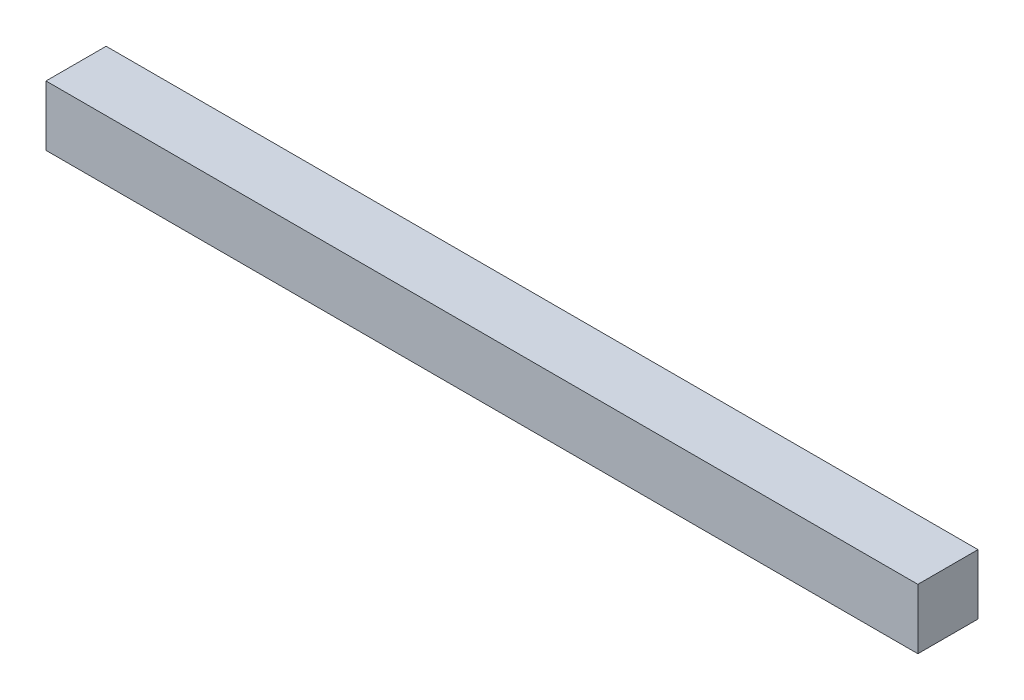
SolidWorks part; units mm, degrees
ref_plane "Front Plane" through (0, 0, 0) normal (0, 0, 1) x (1, 0, 0)
ref_plane "Top Plane" through (0, 0, 0) normal (0, 1, 0) x (1, 0, 0)
ref_plane "Right Plane" through (0, 0, 0) normal (1, 0, 0) x (0, 0, -1)
other "Configuration Table"
sketch "Sketch1" plane through (0, 0, 0) normal (0, 0, 1) x (1, 0, 0)
  line L1 (-58, 22) -> (58, 22)
  line L2 (-58, 22) -> (-58, 30)
  line L3 (-58, 30) -> (58, 30)
  line L4 (58, 22) -> (58, 30)
extrude "LRAF_capraz_cubuk_8x8_1" add sketch "Sketch1" against normal blind 8 from offset 52 separate body
